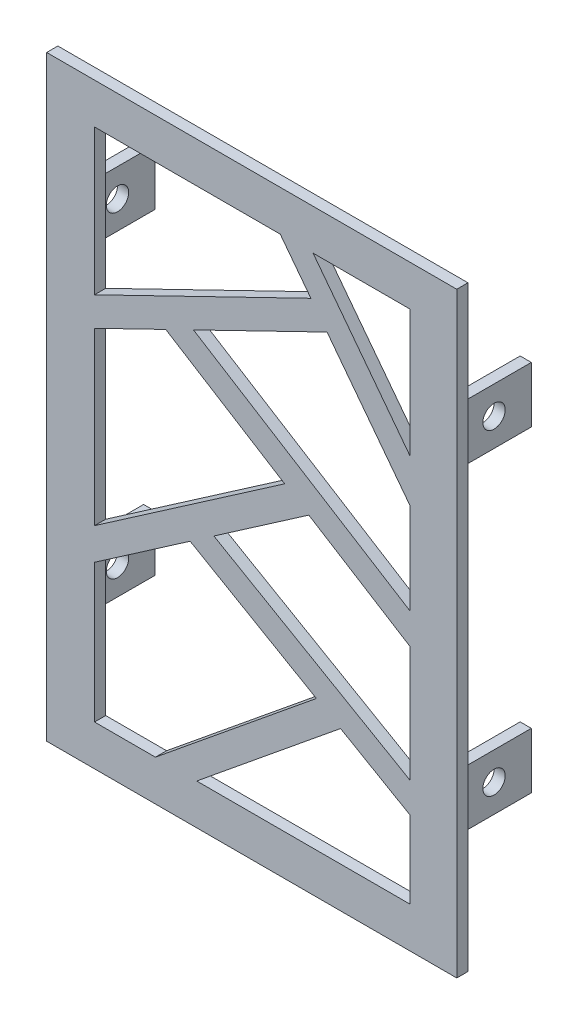
SolidWorks part; units mm, degrees
ref_plane "Front Plane" through (0, 0, 0) normal (0, 0, 1) x (1, 0, 0)
ref_plane "Top Plane" through (0, 0, 0) normal (0, 1, 0) x (1, 0, 0)
ref_plane "Right Plane" through (0, 0, 0) normal (1, 0, 0) x (0, 0, -1)
sketch "Sketch1" plane through (0, 0, 0) normal (0, 0, 1) x (1, 0, 0)
  line L1 (0, 0) -> (110, 0)
  line L2 (0, 0) -> (0, 160)
  line L3 (0, 160) -> (110, 160)
  line L4 (110, 0) -> (110, 160)
  dimension "D1" = 160
  dimension "D2" = 110
extrude "Boss-Extrude1" add sketch "Sketch1" along normal blind 3
sketch "Sketch2" plane through (0, 0, 0) normal (0, 0, -1) x (-1, 0, 0)
  line L0 (0, 160) -> (0, 0) construction
  line L1 (-6, 130) -> (-3, 130)
  line L2 (-6, 130) -> (-6, 115)
  line L3 (-6, 115) -> (-3, 115)
  line L4 (-3, 130) -> (-3, 115)
  line L5 (-6, 45) -> (-3, 45)
  line L6 (-6, 45) -> (-6, 30)
  line L7 (-6, 30) -> (-3, 30)
  line L8 (-3, 45) -> (-3, 30)
  line L9 (-110, 160) -> (0, 160) construction
  line L10 (0, 0) -> (-110, 0) construction
  line L11 (-55, 224.1792) -> (-55, -65.648) construction
  line L13 (-104, 45) -> (-104, 30)
  line L14 (-104, 30) -> (-107, 30)
  line L15 (-107, 45) -> (-107, 30)
  line L16 (-104, 45) -> (-107, 45)
  line L17 (-104, 115) -> (-107, 115)
  line L18 (-107, 130) -> (-107, 115)
  line L19 (-104, 130) -> (-104, 115)
  line L20 (-104, 130) -> (-107, 130)
  dimension "D1" = 3
  dimension "D2" = 3
  dimension "D3" = 15
  dimension "D4" = 30
  dimension "D5" = 3
  dimension "D6" = 3
  dimension "D7" = 15
  dimension "D8" = 30
  dimension "D9" = 55
extrude "Boss-Extrude2" add sketch "Sketch2" along normal blind 20
fillet "Fillet1" radius 5 4 edges at (6, 37.5, 0) (6, 122.5, 0) (104, 37.5, 0) (104, 122.5, 0)
sketch "Sketch3" plane through (107, 0, 0) normal (1, 0, 0) x (0, 0, -1)
  line L0 (20, 30) -> (0, 30) construction
  line L1 (20, 45) -> (20, 30) construction
  line L2 (20, 130) -> (20, 115) construction
  line L3 (20, 130) -> (0, 130) construction
  circle A0 centre (10, 122.5) radius 3
  circle A1 centre (10, 37.5) radius 3
  dimension "D1" = 6
  dimension "D5" = 6
  dimension "D2" = 7.5
  dimension "D3" = 10
  dimension "D4" = 10
  dimension "D6" = 7.5
extrude "Cut-Extrude1" cut sketch "Sketch3" against normal blind 120
sketch "Sketch4" plane through (0, 0, 0) normal (0, 0, -1) x (-1, 0, 0)
  line L0 (-67.0556, 149.1171) -> (-97.4046, 109.3106)
  line L1 (-97.4046, 149.1171) -> (-12.835, 149.1171)
  line L2 (-97.4046, 149.1171) -> (-97.4046, 10.8829)
  line L3 (-97.4046, 10.8829) -> (-12.835, 10.8829)
  line L4 (-12.835, 149.1171) -> (-12.835, 10.8829)
  line L5 (-76.2556, 137.0501) -> (-12.835, 106.2354)
  line L6 (-32.1546, 115.6224) -> (-97.4046, 74.8999)
  line L7 (-70.2182, 91.8669) -> (-12.835, 52.2411)
  line L8 (-38.3153, 69.8365) -> (-97.4046, 35.6634)
  line L9 (-78.491, 46.6017) -> (-34.7061, 10.8829)
  line L10 (-69.8389, 151.2392) -> (-100.1879, 111.4326)
  line L11 (-80.1615, 135.0566) -> (-9.2077, 100.5817)
  line L12 (-34.0077, 118.5916) -> (-99.2577, 77.8691)
  line L13 (-71.8961, 88.7722) -> (-10.8279, 46.6017)
  line L14 (-40.0675, 72.8663) -> (-99.1568, 38.6932)
  line L15 (-80.7034, 43.8897) -> (-36.9185, 8.1709)
  line L16 (-59.0347, 153.8648) -> (-98.6989, 101.8402)
  line L17 (-74.7261, 140.1982) -> (-11.3054, 109.3835)
  line L18 (-29.5554, 113.1189) -> (-99.1659, 69.675)
  line L19 (-68.2294, 94.747) -> (-10.8462, 55.1211)
  line L20 (-36.4845, 66.8521) -> (-100.2062, 30)
  line L21 (-76.4006, 49.4133) -> (-25.821, 8.1515)
  line L22 (-64.2723, 146.9951) -> (-94.6213, 107.1886) construction
  line L23 (-77.7852, 133.902) -> (-14.3646, 103.0873) construction
  line L24 (-30.3016, 112.6532) -> (-95.5515, 71.9307) construction
  line L25 (-36.5631, 66.8067) -> (-95.6524, 32.6336) construction
  line L26 (-107, 30) -> (-99, 30) construction
  line L27 (-76.2786, 49.3137) -> (-32.4937, 13.5949) construction
  line L28 (-72.207, 88.9869) -> (-14.8238, 49.361) construction
  point P40 (-100.0335, 105.0233)
  point P43 (-59.1972, 153.9886)
  point P44 (-9.2513, 100.492)
  point P47 (-99.2577, 69.675)
  point P50 (-99.1568, 30)
  point P55 (-25.821, 8.1709)
  point P58 (-10.8462, 46.6017)
  point P61 (-98.6989, 101.8402)
  point P62 (-80.1615, 135.0566)
  dimension "D1" = 3.5
  dimension "D2" = 3.5
extrude "Cut-Extrude2" cut sketch "Sketch4" against normal blind 10 contours L10 L1 L2 | L11 L16 L2 L12 | L16 L17 L4 L1 | L18 L19 L4 L11 | L13 L18 L2 L14 | L15 L20 L2 L3 | L20 L21 L3 L4 L13
